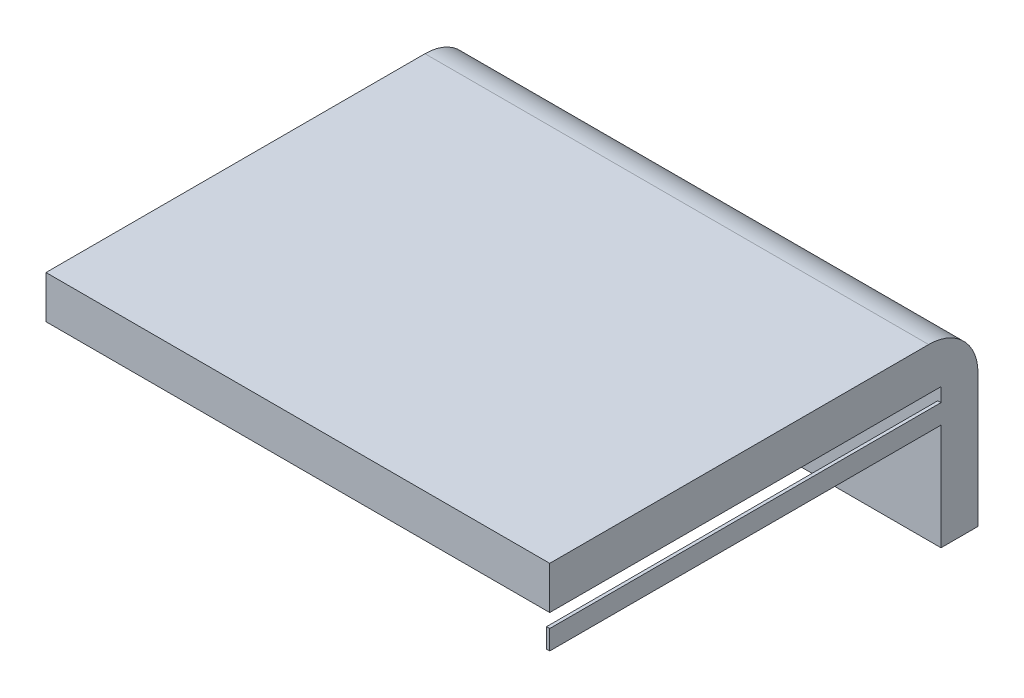
SolidWorks part; units mm, degrees
ref_plane "Front Plane" through (0, 0, 0) normal (0, 0, 1) x (1, 0, 0)
ref_plane "Top Plane" through (0, 0, 0) normal (0, 1, 0) x (1, 0, 0)
ref_plane "Right Plane" through (0, 0, 0) normal (1, 0, 0) x (0, 0, -1)
sketch "Sketch1" plane through (0, 0, 0) normal (0, 1, 0) x (1, 0, 0)
  line L1 (170.1792, 113.0208) -> (374.4792, 113.0208)
  line L2 (170.1792, 113.0208) -> (170.1792, -60.6792)
  line L3 (170.1792, -60.6792) -> (374.4792, -60.6792)
  line L4 (374.4792, 113.0208) -> (374.4792, -60.6792)
  dimension "D1" = 204.3
  dimension "D2" = 173.7
extrude "Boss-Extrude2" add sketch "Sketch1" along normal blind 10
sketch "Sketch4" plane through (0, 0, 0) normal (0, -1, 0) x (-1, 0, 0)
  line L0 (-170.1792, 113.0208) -> (-170.1792, -60.6792) construction
  line L1 (-374.4792, 113.0208) -> (-170.1792, 113.0208)
  line L2 (-374.4792, 113.0208) -> (-374.4792, 98.0208)
  line L3 (-374.4792, 98.0208) -> (-170.1792, 98.0208)
  line L4 (-170.1792, 113.0208) -> (-170.1792, 98.0208)
  dimension "D1" = 15
extrude "Boss-Extrude4" add sketch "Sketch4" along normal blind 68.9
sketch "Sketch5" plane through (0, 0, 0) normal (0, -1, 0) x (1, 0, 0)
  line L0 (170.1792, -98.0208) -> (170.1792, 60.6792) construction
  line L1 (374.4792, 60.6792) -> (170.1792, 60.6792)
  line L2 (374.4792, 60.6792) -> (374.4792, 45.6792)
  line L3 (374.4792, 45.6792) -> (170.1792, 45.6792)
  line L4 (170.1792, 60.6792) -> (170.1792, 45.6792)
  dimension "D1" = 15
sketch "Sketch6" plane through (0, 0, -98.0208) normal (0, 0, 1) x (1, 0, 0)
  line L0 (374.4792, -68.9) -> (374.4792, 0) construction
  line L1 (170.1792, -68.9) -> (374.4792, -68.9)
  line L2 (170.1792, -68.9) -> (170.1792, -63.9)
  line L3 (170.1792, -63.9) -> (374.4792, -63.9)
  line L4 (374.4792, -68.9) -> (374.4792, -63.9)
  dimension "D1" = 5
extrude "Cut-Extrude1" cut sketch "Sketch6" against normal blind 26
extrude "Boss-Extrude6" add sketch "Sketch5" along normal blind 7.3 contours L3 L4 L1 L2
fillet "Fillet1" radius 20 1 edges at (272.3292, 10, -113.0208)
sketch "Sketch7" plane through (374.4792, 0, 0) normal (1, 0, 0) x (0, 0, -1)
  line L1 (-45.6792, -7.3) -> (98.0208, -7.3)
  line L2 (-45.6792, -7.3) -> (-45.6792, 0)
  line L3 (-45.6792, 0) -> (98.0208, 0)
  line L4 (98.0208, -7.3) -> (98.0208, 0)
extrude "Boss-Extrude7" add sketch "Sketch7" against normal blind 204.3
sketch "Sketch9" plane through (374.4792, 0, 0) normal (1, 0, 0) x (0, 0, -1)
  line L0 (98.0208, -63.9) -> (98.0208, -7.3) construction
  line L1 (-60.6792, -7.3) -> (98.0208, -7.3)
  line L2 (-60.6792, -7.3) -> (-60.6792, -26.4)
  line L3 (-60.6792, -26.4) -> (98.0208, -26.4)
  line L4 (98.0208, -7.3) -> (98.0208, -26.4)
  line L6 (-60.6792, -12.9) -> (98.0532, -12.9)
  line L7 (-60.6792, -12.9) -> (-60.6792, -20.8)
  line L8 (-60.6792, -20.8) -> (98.0532, -20.8)
  line L9 (98.0532, -12.9) -> (98.0532, -20.8)
  dimension "D1" = 19.1
  dimension "D2" = 5.6
  dimension "D3" = 7.9
extrude "Boss-Extrude9" add sketch "Sketch9" against normal blind 1.3 contours L2 L8 L4 L6
